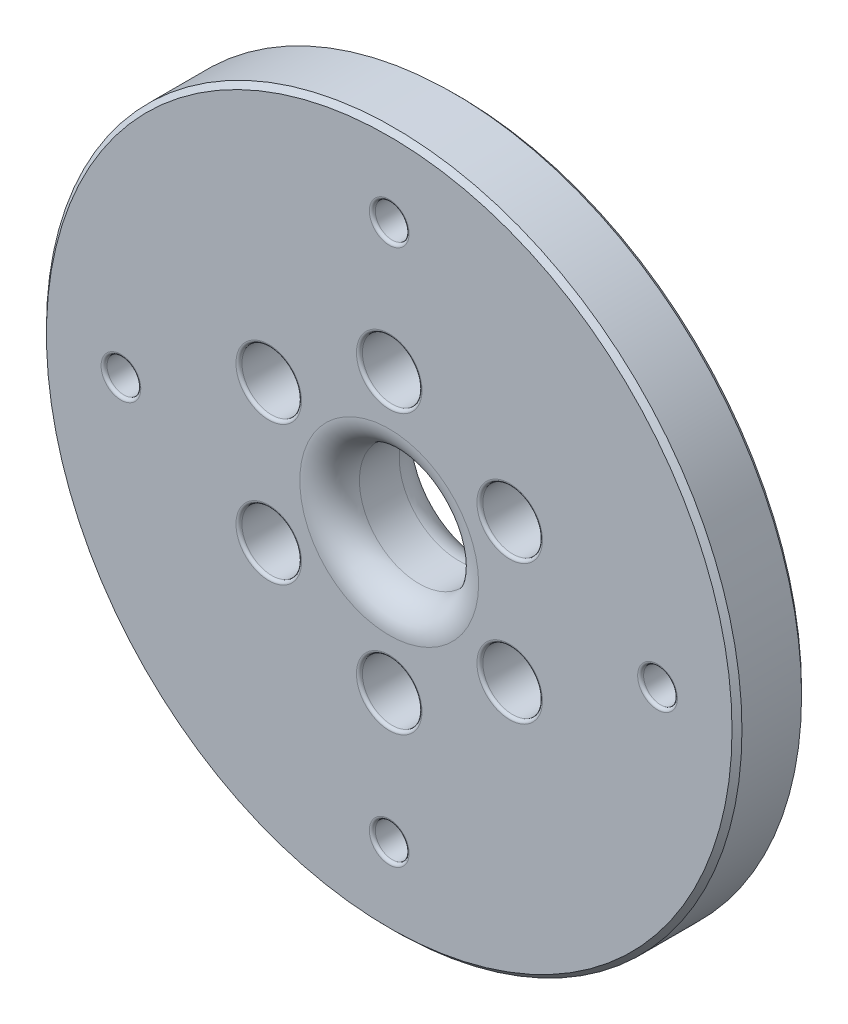
SolidWorks part; units mm, degrees
ref_plane "정면" through (0, 0, 0) normal (0, 0, 1) x (1, 0, 0)
ref_plane "윗면" through (0, 0, 0) normal (0, 1, 0) x (1, 0, 0)
ref_plane "우측면" through (0, 0, 0) normal (1, 0, 0) x (0, 0, -1)
sketch "스케치2" plane through (0, 0, 0) normal (0, 0, 1) x (1, 0, 0)
  circle A0 centre (0, 0) radius 18.5
  dimension "D1" = 37
extrude "보스-돌출1" add sketch "스케치2" along normal blind 3
sketch "스케치3" plane through (0, 0, 3) normal (0, 0, 1) x (1, 0, 0)
  circle A0 centre (0, 0) radius 35
  dimension "D1" = 70
extrude "보스-돌출2" add sketch "스케치3" along normal blind 7
hole_wizard "M3 육각 소켓 머리 캡 나사용 카운터보어1" positions "스케치4" profile "스케치5" counterbore size "M3" standard "ISO"
sketch "스케치4" plane through (0, 0, 10) normal (0, 0, 1) x (1, 0, 0)
  point P0 (12.1244, -7)
  point P5 (12.1244, 7)
  point P8 (0, 14)
  point P11 (-12.1244, 7)
  point P14 (0, -14)
  point P17 (-12.1244, -7)
sketch "스케치5" plane through (12.1244, -7, 10) normal (1, 0, 0) x (0, -1, 0)
  line L0 (0, 0) -> (0, 15)
  line L1 (0, 15) -> (1.6, 14.0386)
  line L2 (1.6, 14.0386) -> (1.6, 5)
  line L3 (1.6, 5) -> (3, 5)
  line L4 (3, 5) -> (3, 0)
  line L5 (3, 0) -> (0, 0)
  line L10 (0, 15) -> (-1.6, 14.0386) construction
  line L11 (0, -6.35) -> (0, 107.95) construction
  dimension "구멍 지름" = 3.2
  dimension "구멍 깊이" = 15
  dimension "카운터보어 지름" = 6
  dimension "카운터보어 깊이" = 5
  dimension "드릴 각도" = 118
sketch "스케치6" plane through (0, 0, 10) normal (0, 0, 1) x (1, 0, 0)
  circle A0 centre (0, 0) radius 6
  dimension "D1" = 12
extrude "컷-돌출1" cut sketch "스케치6" against normal through all both and the other way through all
fillet "필렛1" radius 1 1 edges at (18.5, 0, 3)
chamfer "모따기1" distance 0.5 angle 45 3 edges at (18.5, 0, 0) (35, 0, 3) (35, 0, 10)
fillet "필렛2" radius 0.3 24 edges at (3, 14, 10) (3, 14, 5) (15.1244, 7, 10) (15.1244, 7, 5) (15.1244, -7, 10) (15.1244, -7, 5) (3, -14, 10) (3, -14, 5) (1.6, 14, 0) (1.6, 14, 5) (13.7244, 7, 0) (13.7244, 7, 5) (13.7244, -7, 0) (13.7244, -7, 5) (1.6, -14, 0) (1.6, -14, 5) (-10.5244, 7, 0) (-10.5244, 7, 5) (-10.5244, -7, 0) (-10.5244, -7, 5) (-9.1244, -7, 5) (-9.1244, -7, 10) (-9.1244, 7, 5) (-9.1244, 7, 10)
fillet "필렛3" radius 3 1 edges at (6, 0, 10)
fillet "필렛4" radius 3 1 edges at (6, 0, 0)
sketch "스케치7" plane through (0, 0, 3) normal (0, 0, -1) x (-1, 0, 0)
  line L0 (-27, 0) -> (0, -27) construction
  line L1 (0, -27) -> (27, 0) construction
  line L2 (27, 0) -> (0, 27) construction
  line L3 (0, 27) -> (-27, 0) construction
hole_wizard "M3 여유 구멍1" positions "스케치8" profile "스케치9" hole size "M3" standard "ISO" end condition through all
sketch "스케치8" plane through (0, 0, 3) normal (0, 0, -1) x (-1, 0, 0)
  point P0 (0, 27)
  point P3 (27, 0)
  point P6 (0, -27)
  point P9 (-27, 0)
sketch "스케치9" plane through (0, 27, 3) normal (1, 0, 0) x (0, 1, 0)
  line L0 (0, 0) -> (0, 7)
  line L1 (0, 7) -> (1.7, 7)
  line L2 (1.7, 7) -> (1.7, 0)
  line L5 (1.7, 0) -> (0, 0)
  line L11 (0, -6.35) -> (0, 107.95) construction
  dimension "관통 구멍 지름" = 3.4
  dimension "관통 구멍 깊이" = 7
sketch "스케치10" plane through (0, 0, 3) normal (0, 0, -1) x (-1, 0, 0)
  line L6 (-29.725, -2.725) -> (-24.275, -2.725)
  line L7 (-29.725, -2.725) -> (-29.725, 2.725)
  line L8 (-2.725, 24.275) -> (2.725, 24.275)
  line L9 (-2.725, 24.275) -> (-2.725, 29.725)
  line L10 (-2.725, 29.725) -> (2.725, 29.725)
  line L11 (2.725, 24.275) -> (2.725, 29.725)
  line L12 (-2.725, 24.275) -> (2.725, 29.725) construction
  line L13 (-2.725, 29.725) -> (2.725, 24.275) construction
  line L14 (24.275, -2.725) -> (29.725, -2.725)
  line L15 (24.275, -2.725) -> (24.275, 2.725)
  line L16 (24.275, 2.725) -> (29.725, 2.725)
  line L17 (29.725, -2.725) -> (29.725, 2.725)
  line L18 (24.275, -2.725) -> (29.725, 2.725) construction
  line L19 (24.275, 2.725) -> (29.725, -2.725) construction
  line L20 (-2.725, -29.725) -> (2.725, -29.725)
  line L21 (-2.725, -29.725) -> (-2.725, -24.275)
  line L22 (-2.725, -24.275) -> (2.725, -24.275)
  line L23 (2.725, -29.725) -> (2.725, -24.275)
  line L24 (-2.725, -29.725) -> (2.725, -24.275) construction
  line L25 (-2.725, -24.275) -> (2.725, -29.725) construction
  line L26 (-29.725, 2.725) -> (-24.275, 2.725)
  line L27 (-24.275, -2.725) -> (-24.275, 2.725)
  line L28 (-29.725, -2.725) -> (-24.275, 2.725) construction
  line L29 (-29.725, 2.725) -> (-24.275, -2.725) construction
  point P0 (-27, 0)
  point P7 (0, 27)
  point P12 (27, 0)
  point P18 (0, -27)
  dimension "D1" = 5.45
  dimension "D2" = 5.45
  dimension "D3" = 5.45
  dimension "D4" = 5.45
  dimension "D5" = 5.45
  dimension "D6" = 5.45
  dimension "D7" = 5.45
  dimension "D8" = 5.45
extrude "컷-돌출2" cut sketch "스케치10" against normal blind 2.45
fillet "필렛5" radius 0.3 56 edges at (25.3, 0, 10) (-1.7, -27, 10) (-28.7, 0, 10) (-1.7, 27, 10) (-2.725, -29.725, 4.225) (2.725, -29.725, 4.225) (2.725, -24.275, 4.225) (-2.725, -24.275, 4.225) (0, -29.725, 5.45) (2.725, -27, 5.45) (0, -24.275, 5.45) (-2.725, -27, 5.45) (0, -29.725, 3) (2.725, -27, 3) (0, -24.275, 3) (-2.725, -27, 3) (-29.725, -2.725, 4.225) (-24.275, -2.725, 4.225) (-24.275, 2.725, 4.225) (-29.725, 2.725, 4.225) (-27, -2.725, 5.45) (-24.275, 0, 5.45) (-27, 2.725, 5.45) (-29.725, 0, 5.45) (-27, -2.725, 3) (-24.275, 0, 3) (-27, 2.725, 3) (-29.725, 0, 3) (-2.725, 24.275, 4.225) (2.725, 24.275, 4.225) (2.725, 29.725, 4.225) (-2.725, 29.725, 4.225) (0, 24.275, 5.45) (2.725, 27, 5.45) (0, 29.725, 5.45) (-2.725, 27, 5.45) (0, 24.275, 3) (2.725, 27, 3) (0, 29.725, 3) (-2.725, 27, 3) (24.275, 0, 3) (24.275, 0, 5.45) (29.725, 0, 5.45) (24.275, 2.725, 4.225) (29.725, 2.725, 4.225) (29.725, -2.725, 4.225) (24.275, -2.725, 4.225) (1.7, 27, 5.45) (-25.3, 0, 5.45) (1.7, -27, 5.45) (28.7, 0, 5.45) (29.725, 0, 3) (27, 2.725, 3) (27, 2.725, 5.45) (27, -2.725, 5.45) (27, -2.725, 3)
